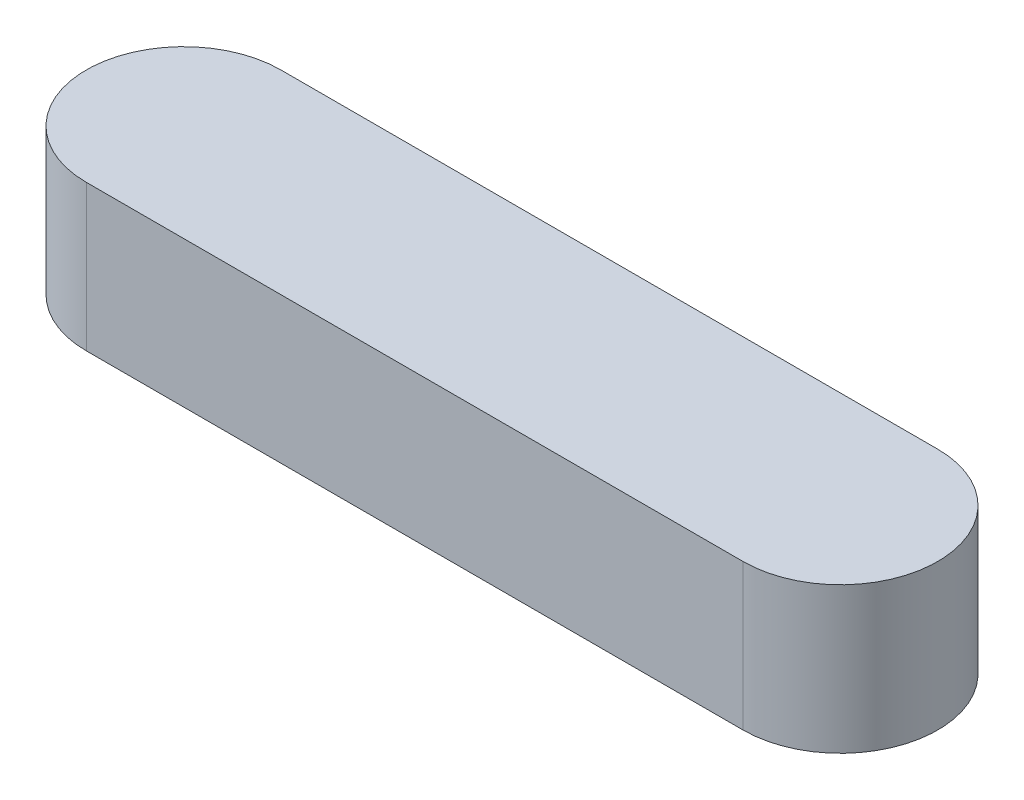
SolidWorks part; units mm, degrees
material "Cast Alloy Steel"
ref_plane "Front Plane" through (0, 0, 0) normal (0, 0, 1) x (1, 0, 0)
ref_plane "Top Plane" through (0, 0, 0) normal (0, 1, 0) x (1, 0, 0)
ref_plane "Right Plane" through (0, 0, 0) normal (1, 0, 0) x (0, 0, -1)
sketch "Sketch1" plane through (0, 0, 0) normal (0, 1, 0) x (1, 0, 0)
  line L0 (-35, 0) -> (35, 0) construction
  line L1 (-27, 0) -> (27, 0) construction
  line L2 (-27, 8) -> (27, 8)
  line L3 (-27, -8) -> (27, -8)
  arc A0 (-27, 8) -> (-27, -8) centre (-27, 0) ccw
  arc A1 (27, -8) -> (27, 8) centre (27, 0) ccw
  point P4 (0, 0)
  point P7 (0, 0)
  dimension "D" = 8
  dimension "L" = 70
extrude "Boss-Extrude1" add sketch "Sketch1" along normal blind 12
sketch "Sketch2" plane through (0, 12, 0) normal (0, 1, 0) x (1, 0, 0)
  line L0 (27, 8) -> (-27, 8) construction
  line L1 (0, 8) -> (35, 8)
  line L2 (0, 8) -> (0, -8)
  line L3 (0, -8) -> (35, -8)
  line L4 (35, 8) -> (35, -8)
  line L5 (-27, -8) -> (27, -8) construction
  arc A0 (27, -8) -> (27, 8) centre (27, 0) ccw construction
extrude "Cut-Extrude1" [suppressed] cut sketch "Sketch2" against normal through all
equation "\"L\"= 70"
equation "\"D\"= 8"
equation "\"H\"= 12"
equation "\"Cut-Extrude1\"= IIF ( \"L\" = 160 , \"unsuppressed\" , IIF ( \"L\" = 100 , \"unsuppressed\" , \"suppressed\" ) )"
equation "\"L@Sketch1\"=\"L\""
equation "\"D@Sketch1\"=\"D\""
equation "\"H@Boss-Extrude1\"=\"H\""
